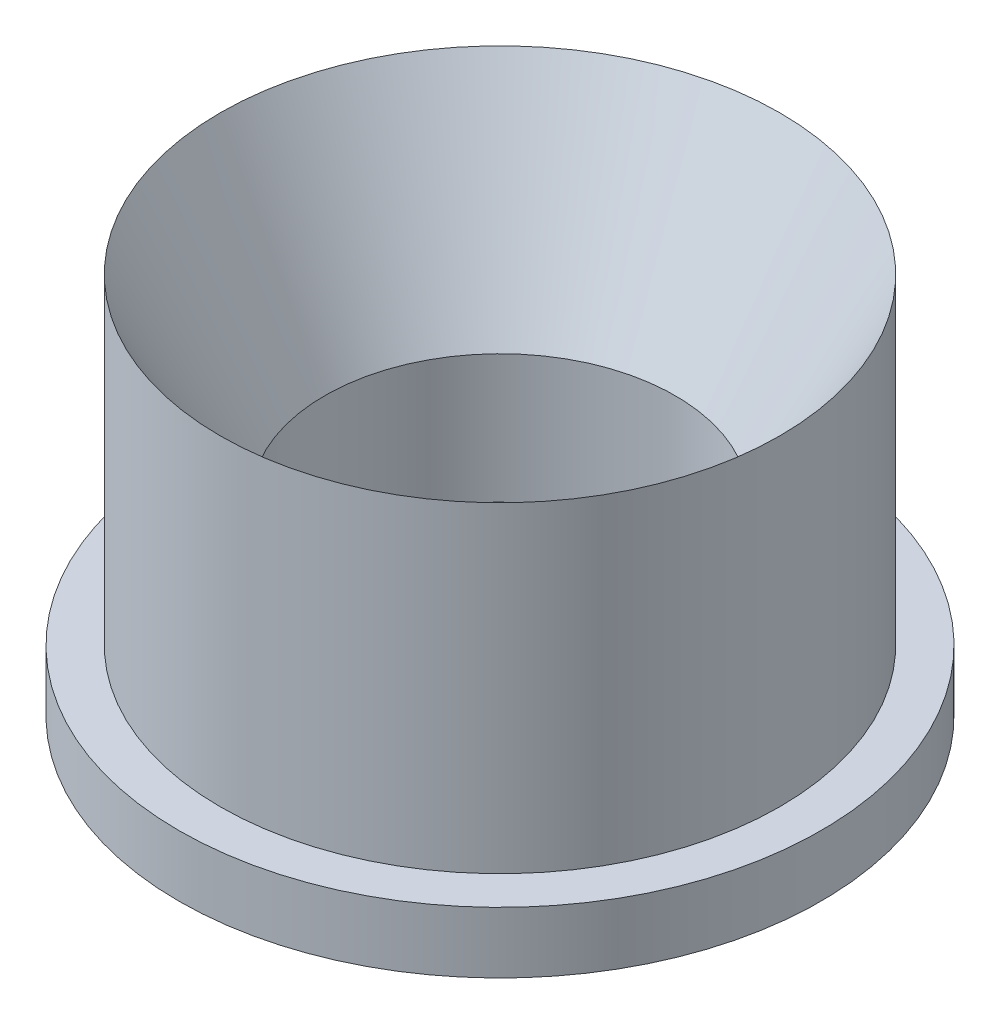
SolidWorks part; units mm, degrees
ref_plane "Front Plane" through (0, 0, 0) normal (1, 0, 0) x (0, 1, 0)
ref_plane "Top Plane" through (0, 0, 0) normal (0, 0, 1) x (0, 1, 0)
ref_plane "Right Plane" through (0, 0, 0) normal (0, 1, 0) x (-1, 0, 0)
sketch "Sketch2" plane through (0, 0, 0) normal (0, 0, 1) x (0, 1, 0)
  line L0 (-9.525, 49.9725) -> (-9.525, 29.1925)
  line L1 (0, 49.9725) -> (-9.525, 49.9725)
  line L2 (0, 49.9725) -> (0, 43.554)
  line L10 (105.2339, 49.9725) -> (0, 49.9725) construction
  line L11 (0, 49.9725) -> (0, 10.4526) construction
  line L12 (0, 27.2875) -> (20, 27.2875)
  line L13 (20, 27.2875) -> (20, 43.554)
  line L14 (200, 43.554) -> (0, 43.554) construction
  line L15 (20, 43.554) -> (0, 43.554)
  line L17 (20, 27.2875) -> (50, 43.554)
  line L18 (50, 43.554) -> (20, 43.554)
  line L19 (562.356, 26.9875) -> (0, 26.9875) construction
  line L20 (20, 43.554) -> (20, 27.2875)
  line L22 (-9.525, 29.1925) -> (0, 29.1925)
  line L23 (0, 29.1925) -> (0, 49.9725)
  line L24 (0, 27.2875) -> (0, 29.1925)
  line L25 (-9.525, 28.8925) -> (-9.525, -28.8925) construction
  line L26 (-9.525, 28.8925) -> (-9.525, -28.8925)
  dimension "D1" = 20
  dimension "D2" = 30
  dimension "D3" = 0.3
  dimension "D4" = 0.3
ref_axis "Axis1" through (0, 52.9763, 0) along (0, -1, 0)
revolve "Revolve1" add sketch "Sketch2" angle 360 about axis through (0, 52.9763, 0) along (0, -1, 0)
